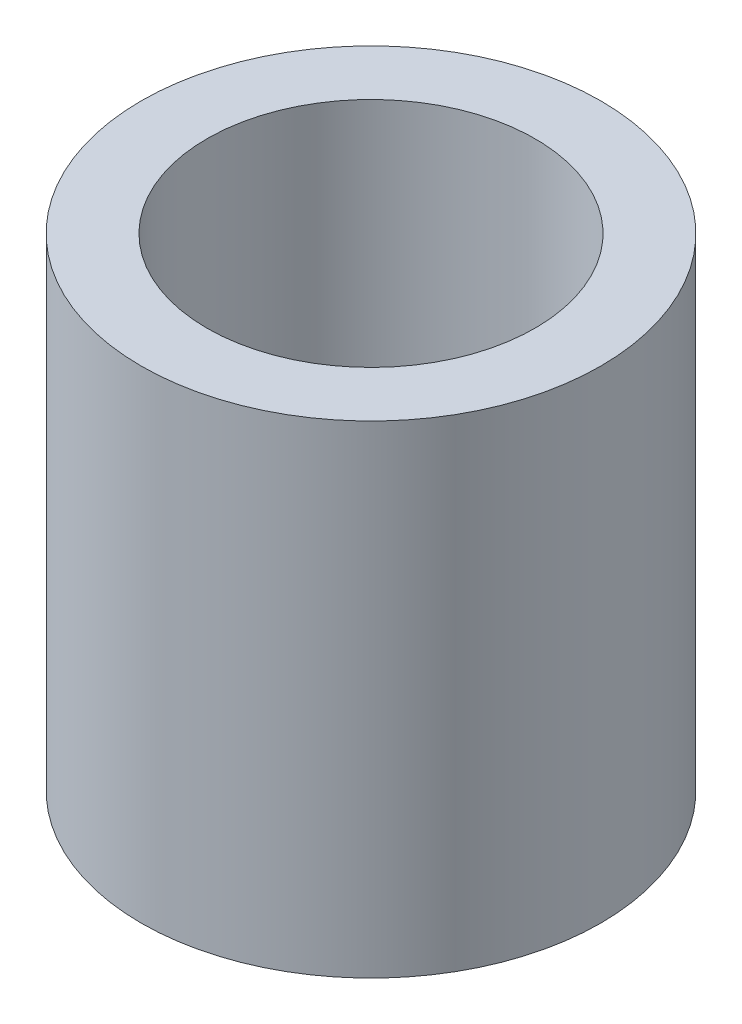
SolidWorks part; units mm, degrees
ref_plane "Front Plane" through (0, 0, 0) normal (0, 0, 1) x (1, 0, 0)
ref_plane "Top Plane" through (0, 0, 0) normal (0, 1, 0) x (1, 0, 0)
ref_plane "Right Plane" through (0, 0, 0) normal (1, 0, 0) x (0, 0, -1)
sketch "Sketch1" plane through (0, 0, 0) normal (0, 1, 0) x (1, 0, 0)
  circle A0 centre (0, 0) radius 2.5
  circle A1 centre (0, 0) radius 3.5
  dimension "D1" = 5
  dimension "D2" = 7
extrude "Boss-Extrude1" add sketch "Sketch1" along normal blind 7.35
